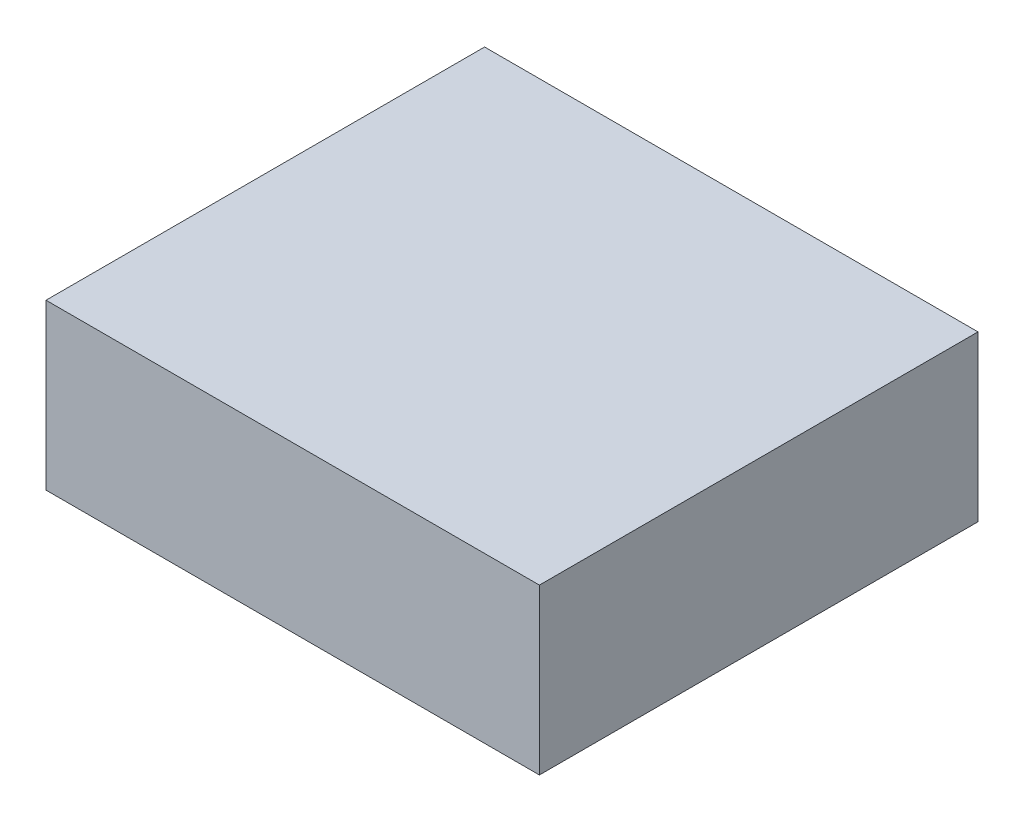
SolidWorks part; units mm, degrees
ref_plane "Front Plane" through (0, 0, 0) normal (0, 0, 1) x (1, 0, 0)
ref_plane "Top Plane" through (0, 0, 0) normal (0, 1, 0) x (1, 0, 0)
ref_plane "Right Plane" through (0, 0, 0) normal (1, 0, 0) x (0, 0, -1)
sketch "Sketch1" plane through (0, 0, 0) normal (0, 0, 1) x (1, 0, 0)
  line L1 (-850, -230) -> (50, -230)
  line L2 (-850, -230) -> (-850, 70)
  line L3 (-850, 70) -> (50, 70)
  line L4 (50, -230) -> (50, 70)
extrude "Boss-Extrude1" add sketch "Sketch1" along normal blind 800 from offset 1240
